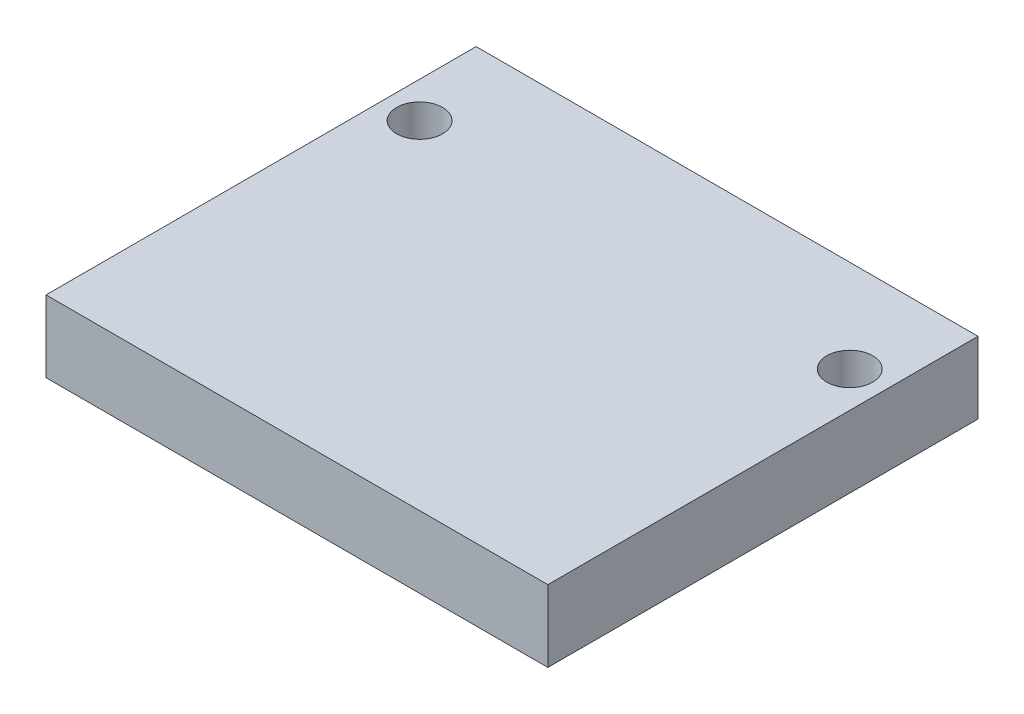
SolidWorks part; units mm, degrees
ref_plane "Front Plane" through (0, 0, 0) normal (0, 0, 1) x (1, 0, 0)
ref_plane "Top Plane" through (0, 0, 0) normal (0, 1, 0) x (1, 0, 0)
ref_plane "Right Plane" through (0, 0, 0) normal (1, 0, 0) x (0, 0, -1)
sketch "草图1" plane through (0, 0, 0) normal (0, 0, 1) x (1, 0, 0)
  line L1 (-17.5, 2.5) -> (17.5, 2.5)
  line L2 (-17.5, 2.5) -> (-17.5, -2.5)
  line L3 (-17.5, -2.5) -> (17.5, -2.5)
  line L4 (17.5, 2.5) -> (17.5, -2.5)
  line L5 (-17.5, 2.5) -> (17.5, -2.5) construction
  line L6 (-17.5, -2.5) -> (17.5, 2.5) construction
  point P0 (0, 0)
  dimension "D1" = 5
  dimension "D2" = 35
extrude "凸台-拉伸1" add sketch "草图1" along normal blind 30
sketch "草图2" plane through (0, 2.5, 0) normal (0, 1, 0) x (1, 0, 0)
  circle A0 centre (15, -6.445) radius 1.6
  circle A1 centre (-15, -6.445) radius 1.6
  dimension "D1" = 3.2
extrude "切除-拉伸1" cut sketch "草图2" against normal blind 10
sketch "草图4" plane through (-17.5, 0, 0) normal (-1, 0, 0) x (0, 0, 1)
  line L0 (30, -2.5) -> (0, -2.5) construction
  line L1 (16.445, -2.5) -> (16.445, -7.5) construction
  line L2 (29.445, -7.5) -> (29.445, -2.5) construction
  line L4 (30, 2.5) -> (29.445, 2.5)
  line L5 (30, 2.5) -> (30, -2.5)
  line L6 (30, -2.5) -> (29.445, -2.5)
  line L7 (29.445, 2.5) -> (29.445, -2.5)
  arc A0 (16.445, -2.5) -> (29.445, -2.5) centre (22.945, -16.0185) cw
  line M2 (0, -2.5) -> (30, -2.5)
  line M3 (30, -2.5) -> (30, 2.5)
  line M4 (30, 2.5) -> (0, 2.5)
  dimension "D1" = 15
extrude "切除-拉伸2" [suppressed] cut sketch "草图4" against normal through all contours A0 M2 | L7 M4 M2 M3
